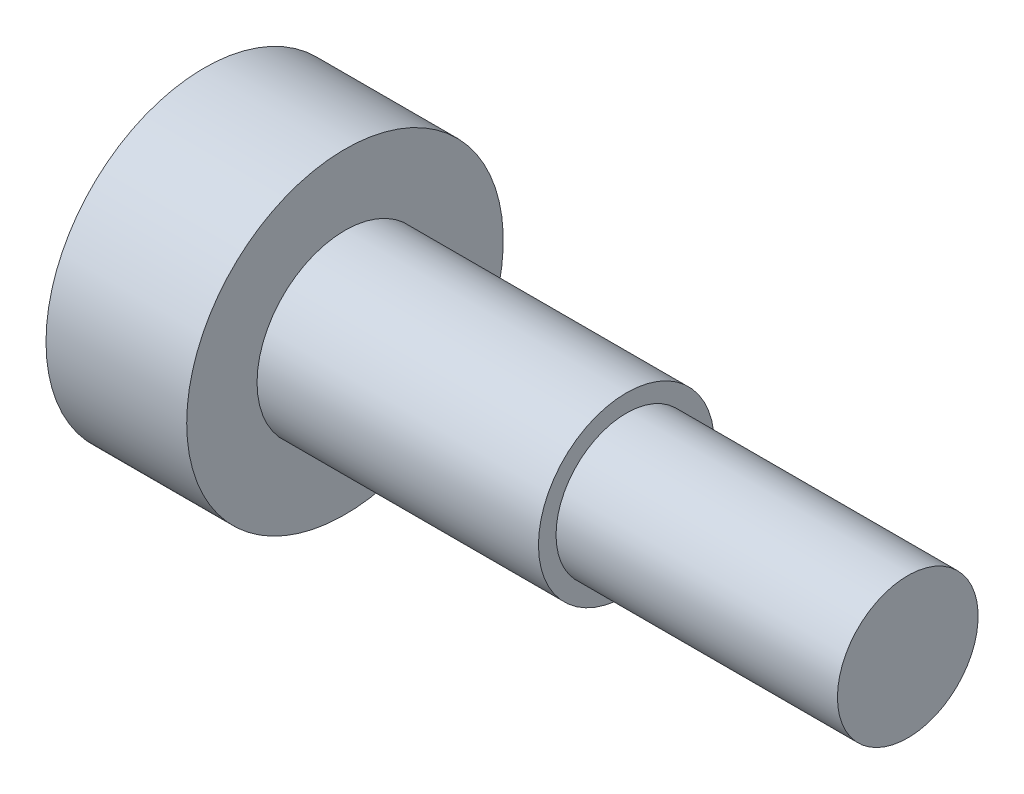
SolidWorks part; units mm, degrees
material "STAINLESS STEEL, 304"
ref_plane "Front Plane" through (0, 0, 0) normal (0, 0, 1) x (1, 0, 0)
ref_plane "Top Plane" through (0, 0, 0) normal (0, 1, 0) x (1, 0, 0)
ref_plane "Right Plane" through (0, 0, 0) normal (1, 0, 0) x (0, 0, -1)
sketch "Sketch1" plane through (0, 0, 0) normal (0, 0, 1) x (1, 0, 0)
  line L2 (-20, 0) -> (0, 0) construction
  line L3 (4, 4.5) -> (0, 4.5)
  line L6 (20, 0) -> (0, 0)
  line L11 (4, 4.5) -> (4, 2.5)
  line L14 (0, 0) -> (0, 4.5)
  line L23 (12, 2.5) -> (4, 2.5)
  line L27 (12, 2.5) -> (12, 2)
  line L39 (20, 2) -> (12, 2)
  line L45 (20, 2) -> (20, 0)
  dimension "D1" = 9
  dimension "D2" = 4
  dimension "D3" = 5
  dimension "D6" = 4
  dimension "D7" = 8
  dimension "D8" = 8
revolve "Revolve1" add sketch "Sketch1" angle 360 about L2
cosmetic thread "Cosmetic Thread1" parameters "D2"=3.22
sketch "Sketch2" plane through (0, 0, 0) normal (-1, 0, 0) x (0, 0, 1)
  line L1 (1.4434, 0) -> (0.7217, 1.25)
  line L2 (0.7217, 1.25) -> (-0.7217, 1.25)
  line L3 (-0.7217, 1.25) -> (-1.4434, 0)
  line L4 (-1.4434, 0) -> (-0.7217, -1.25)
  line L5 (-0.7217, -1.25) -> (0.7217, -1.25)
  line L6 (0.7217, -1.25) -> (1.4434, 0)
  circle A0 centre (0, 0) radius 1.25 construction
  dimension "D1" = 2.5
extrude "Cut-Extrude1" cut sketch "Sketch2" against normal blind 2.5
